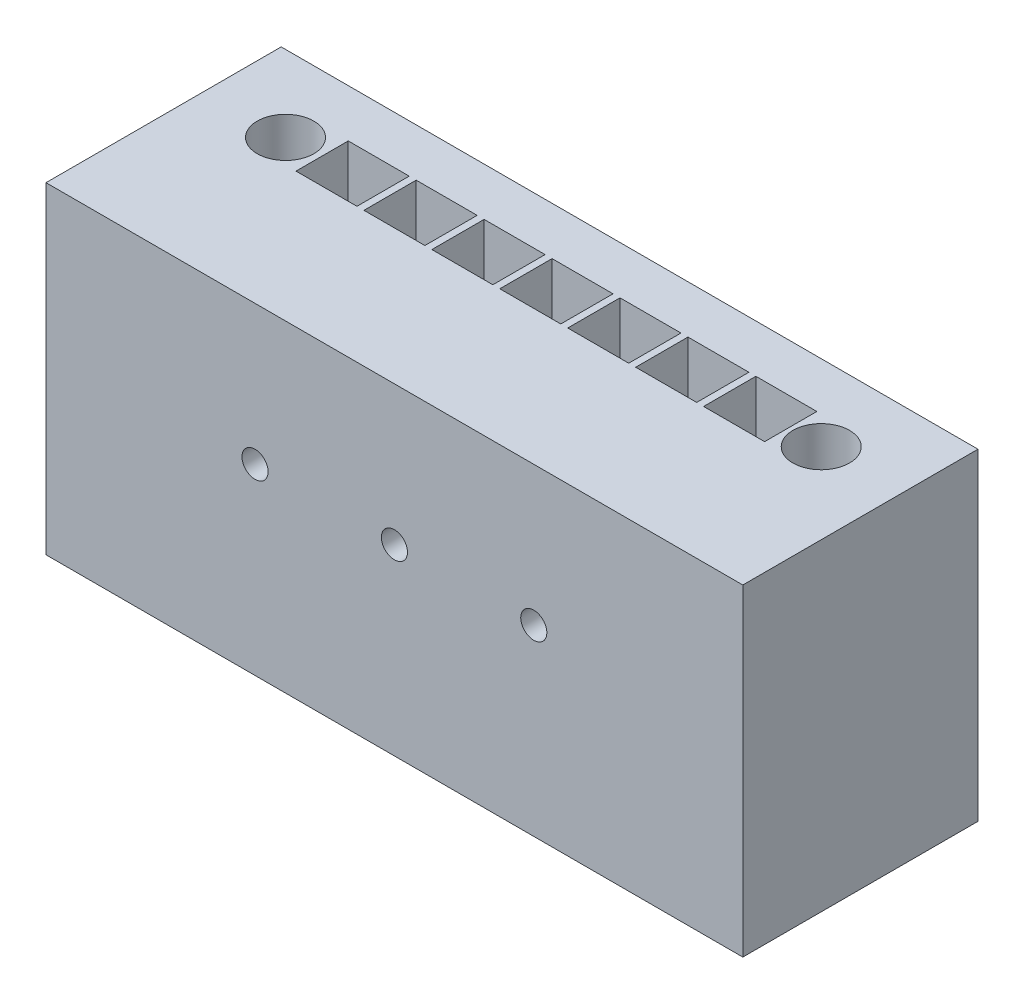
SolidWorks part; units mm, degrees
material "6063-O"
ref_plane "Спереди" through (0, 0, 0) normal (0, 0, 1) x (1, 0, 0)
ref_plane "Сверху" through (0, 0, 0) normal (0, 1, 0) x (1, 0, 0)
ref_plane "Справа" through (0, 0, 0) normal (1, 0, 0) x (0, 0, -1)
ref_plane "Плоскость4" through (0, 0, 0) normal (0, 0, -1) x (-1, 0, 0)
sketch "Эскиз1" plane through (0, 0, 0) normal (0, 0, -1) x (-1, 0, 0)
  line L0 (-40, 0) -> (-40, -37)
  line L1 (-40, -37) -> (40, -37)
  line L2 (40, -37) -> (40, 0)
  line L3 (40, 0) -> (-40, 0)
extrude "Бобышка-Вытянуть1" add sketch "Эскиз1" against normal blind 27
sketch "Эскиз2" plane through (0, -37, 0) normal (0, -1, 0) x (1, 0, 0)
  line L0 (-19.8, 11.5) -> (-26.8, 11.5)
  line L1 (-26.8, 11.5) -> (-26.8, 5.5)
  line L2 (-26.8, 5.5) -> (-19.8, 5.5)
  line L3 (-19.8, 5.5) -> (-19.8, 11.5)
extrude "Вырез-Вытянуть1" cut sketch "Эскиз2" against normal through all
pattern_linear "Линейный массив1" count 7 spacing 7.8 along (1, 0, 0) of "Вырез-Вытянуть1"
hole_wizard "Диаметр отверстия Ø3.0 (3)1" positions "Эскиз4" profile "Эскиз3" hole size "Ø3.0" standard "Ansi Metric"
sketch "Эскиз4" plane through (0, 0, 11.5) normal (0, 0, -1) x (-1, 0, 0)
  point P0 (-16, -16)
  point P1 (0, -16)
  point P2 (16, -16)
sketch "Эскиз3" plane through (16, -16, 11.5) normal (1, 0, 0) x (0, 1, 0)
  line L0 (0, 0) -> (0, 15.5)
  line L1 (0, 15.5) -> (1.5, 15.5)
  line L2 (1.5, 15.5) -> (1.5, 0)
  line L5 (1.5, 0) -> (0, 0)
  line L11 (0, -6.35) -> (0, 107.95) construction
  dimension "Диаметр сквозного отверстия" = 3
  dimension "Глубина сквозного отверстия" = 15.5
hole_wizard "Диаметр отверстия Ø6.5 (6.5)1" positions "Эскиз6" profile "Эскиз5" hole size "Ø6.5" standard "Ansi Metric"
sketch "Эскиз6" plane through (0, -37, 0) normal (0, -1, 0) x (-1, 0, 0)
  point P0 (30.75, -8.75)
  point P1 (-30.75, -8.75)
sketch "Эскиз5" plane through (-30.75, -37, 8.75) normal (1, 0, 0) x (0, 0, -1)
  line L0 (0, 0) -> (0, 37)
  line L1 (0, 37) -> (3.25, 37)
  line L2 (3.25, 37) -> (3.25, 0)
  line L5 (3.25, 0) -> (0, 0)
  line L11 (0, -6.35) -> (0, 107.95) construction
  dimension "Диаметр сквозного отверстия" = 6.5
  dimension "Глубина сквозного отверстия" = 37
hole_wizard "Диаметр отверстия Ø3.0 (3)2" positions "Эскиз8" profile "Эскиз7" hole size "Ø3.0" standard "Ansi Metric"
sketch "Эскиз8" plane through (0, 0, 5.5) normal (0, 0, 1) x (1, 0, 0)
  point P0 (16, -16)
  point P1 (0, -16)
  point P2 (-16, -16)
sketch "Эскиз7" plane through (16, -16, 5.5) normal (1, 0, 0) x (0, -1, 0)
  line L0 (0, 0) -> (0, 5.5)
  line L1 (0, 5.5) -> (1.5, 5.5)
  line L2 (1.5, 5.5) -> (1.5, 0)
  line L5 (1.5, 0) -> (0, 0)
  line L11 (0, -6.35) -> (0, 107.95) construction
  dimension "Диаметр сквозного отверстия" = 3
  dimension "Глубина сквозного отверстия" = 5.5
